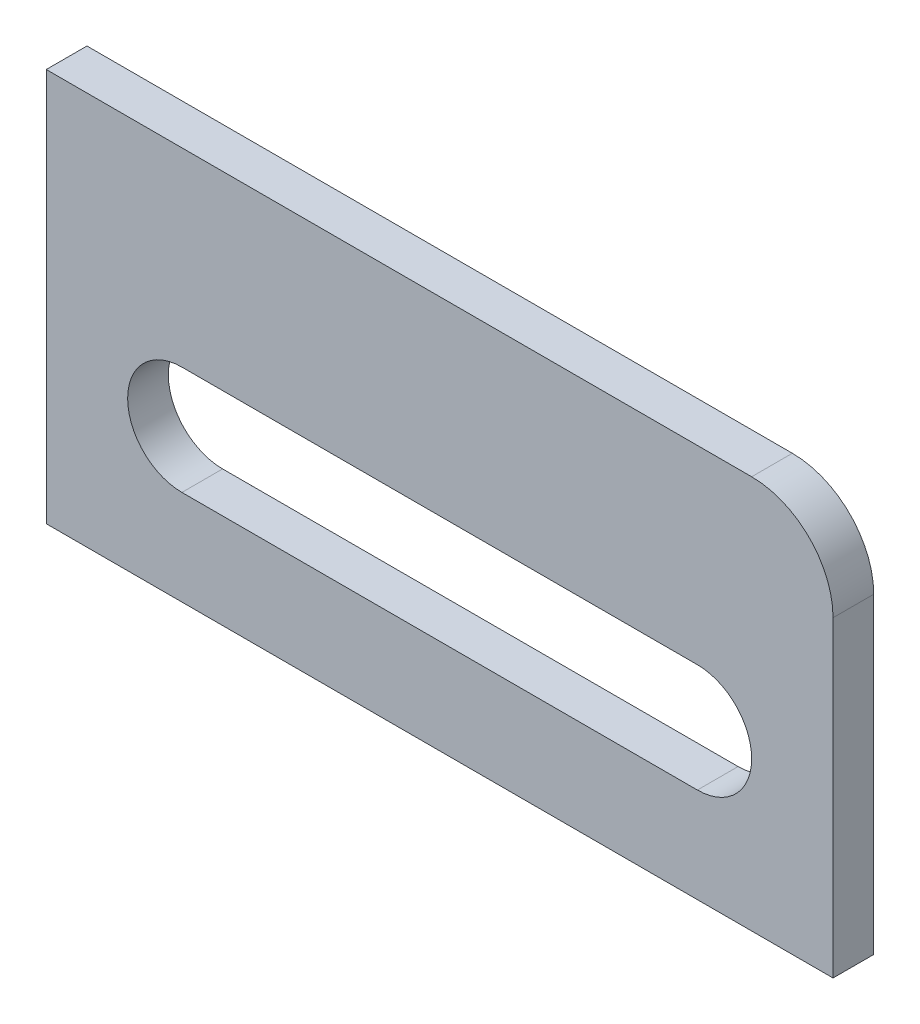
SolidWorks part; units mm, degrees
ref_plane "Front Plane" through (0, 0, 0) normal (0, 0, 1) x (1, 0, 0)
ref_plane "Top Plane" through (0, 0, 0) normal (0, 1, 0) x (1, 0, 0)
ref_plane "Right Plane" through (0, 0, 0) normal (1, 0, 0) x (0, 0, -1)
sketch "Sketch1" plane through (0, 0, 0) normal (0, 0, 1) x (1, 0, 0)
  line L0 (0, 29) -> (52, 29)
  line L5 (58, 0) -> (58, 23)
  line L8 (0, 29) -> (0, 0)
  line L9 (0, 0) -> (58, 0)
  arc A1 (52, 29) -> (58, 23) centre (52, 23) cw
extrude "Boss-Extrude1" add sketch "Sketch1" along normal blind 3
sketch "Sketch4" plane through (0, 0, 3) normal (0, 0, 1) x (1, 0, 0)
  line L0 (0, 11) -> (58, 11) construction
  line L1 (0, 29) -> (0, 0) construction
  line L2 (58, 0) -> (58, 23) construction
  line L3 (0, 0) -> (58, 0) construction
  line L4 (10, 11) -> (10, 29) construction
  line L5 (52, 29) -> (0, 29) construction
  line L6 (48, 11) -> (48, 29) construction
  line L7 (10, 11) -> (48, 11) construction
  line L8 (10, 15) -> (48, 15)
  line L9 (10, 7) -> (48, 7)
  arc A0 (10, 15) -> (10, 7) centre (10, 11) ccw
  arc A1 (48, 7) -> (48, 15) centre (48, 11) ccw
  point P14 (29, 11)
  dimension "D1" = 11
  dimension "D2" = 10
  dimension "D3" = 10
extrude "Cut-Extrude2" cut sketch "Sketch4" against normal blind 10
